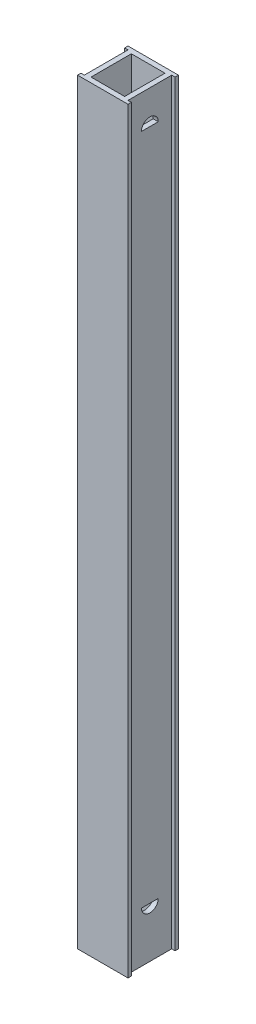
SolidWorks part; units mm, degrees
ref_plane "前视基准面" through (0, 0, 0) normal (0, 0, 1) x (1, 0, 0)
ref_plane "上视基准面" through (0, 0, 0) normal (0, 1, 0) x (1, 0, 0)
ref_plane "右视基准面" through (0, 0, 0) normal (1, 0, 0) x (0, 0, -1)
other "Configuration Table"
sketch "草图1" plane through (0, 0, 0) normal (0, 0, 1) x (1, 0, 0)
  line L0 (0, 0) -> (324.4923, 0) construction
  line L1 (0, 0) -> (0, 279.3401) construction
  line L2 (-15, 225) -> (15, 225)
  line L3 (-15, 225) -> (-15, -225)
  line L4 (-15, -225) -> (15, -225)
  line L5 (15, -225) -> (15, 225)
  point P6 (0, 225)
  point P10 (-15, 0)
  dimension "D1" = 450
  dimension "D2" = 30
extrude "凸台-拉伸1" add sketch "草图1" along normal blind 30
sketch "草图2" plane through (0, 225, 0) normal (0, 1, 0) x (1, 0, 0)
  line L0 (0, 0) -> (0, -20.1827) construction
  line L1 (0, -10) -> (15.4868, -10) construction
  line L2 (-15, -2) -> (-13, -2)
  line L3 (-13, -2) -> (-13, -28)
  line L4 (-13, -28) -> (-15, -28)
  line L5 (15, -30) -> (15, 0) construction
  line L6 (-15, -30) -> (-15, 0) construction
  line L7 (15, -28) -> (15, -2)
  line L8 (-15, -28) -> (-15, -2)
  line L9 (15, 0) -> (-15, 0) construction
  line L10 (15, -30) -> (-15, -30) construction
  line L11 (13, -28) -> (15, -28)
  line L12 (13, -2) -> (13, -28)
  line L13 (15, -2) -> (13, -2)
  dimension "D2" = 2
  dimension "D1" = 2
  dimension "D3" = 2
extrude "切除-拉伸1" cut sketch "草图2" against normal through all
shell "抽壳1" thickness 3
sketch "草图3" plane through (13, 0, 0) normal (1, 0, 0) x (0, 0, -1)
  line L0 (0, 0) -> (170.4874, 0) construction
  line L1 (-15, 225) -> (-15, -46.9872) construction
  line L2 (-20, 205) -> (-10, 205)
  line L3 (-2, 225) -> (-28, 225) construction
  line L4 (-20, -195) -> (-10, -195)
  line L5 (-2, -225) -> (-28, -225) construction
  arc A1 (-10, 205) -> (-20, 205) centre (-15, 205) ccw
  arc A2 (-10, -195) -> (-20, -195) centre (-15, -195) cw
  point P18 (-15, -225)
  dimension "D1" = 20
  dimension "D2" = 5
  dimension "D3" = 30
  dimension "D4" = 5
extrude "切除-拉伸2" cut sketch "草图3" against normal through all
